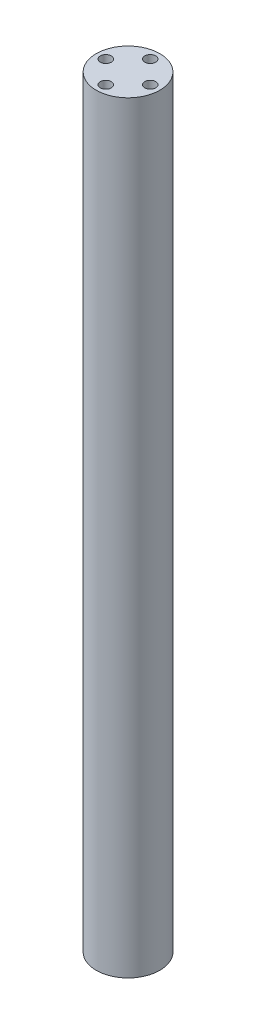
SolidWorks part; units mm, degrees
ref_plane "Front Plane" through (0, 0, 0) normal (0, 0, 1) x (1, 0, 0)
ref_plane "Top Plane" through (0, 0, 0) normal (0, 1, 0) x (1, 0, 0)
ref_plane "Right Plane" through (0, 0, 0) normal (1, 0, 0) x (0, 0, -1)
sketch "Sketch1" plane through (0, 0, 0) normal (0, 1, 0) x (1, 0, 0)
  circle A0 centre (0, 0) radius 12.7
  dimension "D1" = 25.4
extrude "Boss-Extrude1" add sketch "Sketch1" along normal blind 304.8 contours A0
sketch "Sketch2" plane through (0, 0, 0) normal (0, -1, 0) x (1, 0, 0)
  circle A0 centre (0, 0) radius 3.9688
  dimension "D1" = 7.9375
extrude "Cut-Extrude1" cut sketch "Sketch2" against normal blind 76.2 contours A0
sketch "Sketch3" plane through (0, 304.8, 0) normal (0, 1, 0) x (1, 0, 0)
  circle A0 centre (0, 0) radius 8.89 construction
  circle A1 centre (0, 8.89) radius 2.1971
  circle A2 centre (8.89, 0) radius 2.1971
  circle A3 centre (0, -8.89) radius 2.1971
  circle A4 centre (-8.89, 0) radius 2.1971
  point P5 (0, 0)
  point P6 (0, 0)
  point P7 (0, 0)
  point P14 (0, -9.525)
  point P15 (0, 0)
  point P16 (9.525, 0)
  dimension "D1" = 17.78
  dimension "D2" = 4.3942
  dimension "D3" = 4
extrude "Cut-Extrude2" cut sketch "Sketch3" against normal blind 76.2 contours A2 | A3 | A4 | A1
